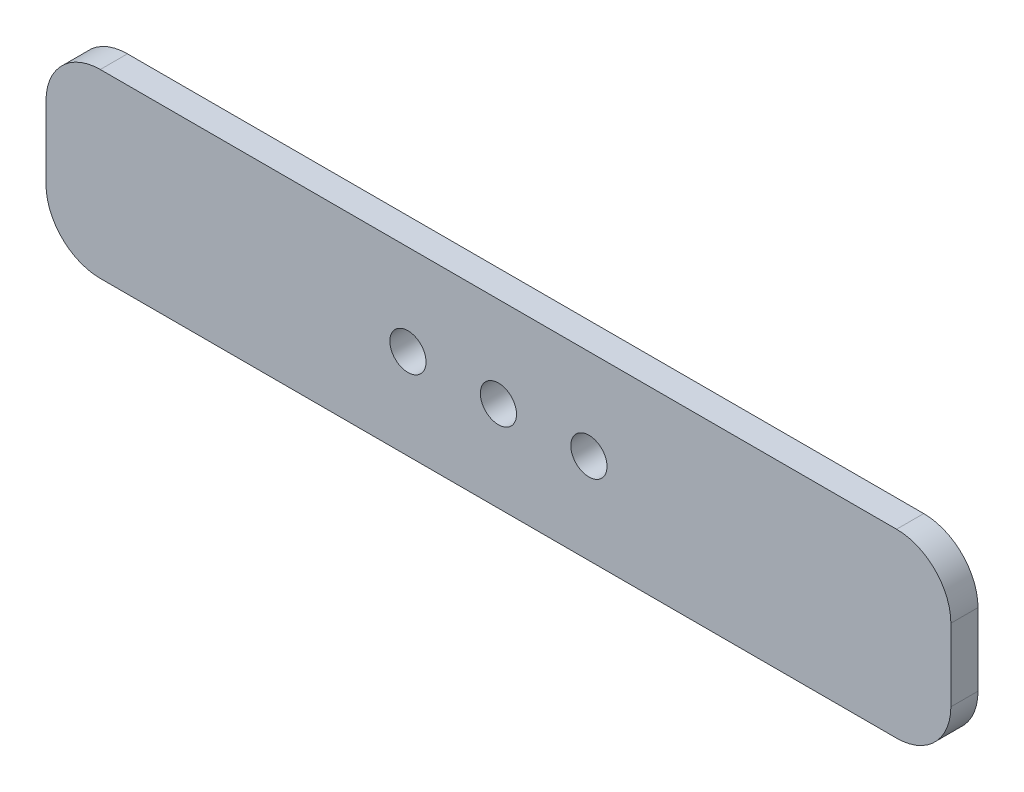
SolidWorks part; units mm, degrees
ref_plane "Plan de face" through (0, 0, 0) normal (0, 0, 1) x (1, 0, 0)
ref_plane "Plan de dessus" through (0, 0, 0) normal (0, 1, 0) x (1, 0, 0)
ref_plane "Plan de droite" through (0, 0, 0) normal (1, 0, 0) x (0, 0, -1)
sketch "Esquisse1" plane through (0, 0, 0) normal (0, 0, 1) x (1, 0, 0)
  line L1 (30, 0) -> (470, 0)
  line L2 (0, 30) -> (0, 70)
  line L3 (30, 100) -> (470, 100)
  line L4 (500, 30) -> (500, 70)
  arc A0 (470, 0) -> (500, 30) centre (470, 30) ccw
  arc A1 (30, 0) -> (0, 30) centre (30, 30) cw
  arc A2 (0, 70) -> (30, 100) centre (30, 70) cw
  arc A3 (500, 70) -> (470, 100) centre (470, 70) ccw
  point P9 (0, 0)
  point P12 (0, 100)
  point P15 (500, 100)
  dimension "D3" = 30
  dimension "D1" = 100
  dimension "D2" = 500
extrude "Boss.-Extru.1" add sketch "Esquisse1" along normal blind 15
sketch "Esquisse2" plane through (0, 0, 15) normal (0, 0, 1) x (1, 0, 0)
  line L0 (200, 50) -> (300, 50) construction
  line L5 (470, 100) -> (30, 100) construction
  line L7 (0, 70) -> (0, 30) construction
  circle A0 centre (200, 50) radius 10
  circle A3 centre (250, 50) radius 10
  circle A4 centre (300, 50) radius 10
  dimension "D1" = 50
  dimension "D3" = 20
  dimension "D2" = 200
  dimension "D4" = 50
  dimension "D5" = 50
extrude "Enlèv. mat.-Extru.2" cut sketch "Esquisse2" against normal through all
sketch "Esquisse3" plane through (0, 0, 0) normal (0, -1, 0) x (1, 0, 0)
  line L0 (30, 0) -> (470, 0) construction
  line L1 (30, 15) -> (30, 0) construction
  line L3 (470, 15) -> (470, 0) construction
  circle A0 centre (60, 7.5) radius 3
  circle A1 centre (440, 7.5) radius 3
  dimension "D1" = 6
  dimension "D3" = 30
  dimension "D4" = 30
  dimension "D5" = 7.5
  dimension "D2" = 7.5
extrude "Enlèv. mat.-Extru.3" cut sketch "Esquisse3" against normal blind 20
sketch "Esquisse4" plane through (0, 0, 15) normal (0, 0, 1) x (1, 0, 0)
  line L0 (470, 100) -> (30, 100) construction
  line L1 (0, 70) -> (0, 30) construction
  text T0 "                          MAQUETTE DE TEST \r\nSYSTEME DE CONTROLE DE TEMPERATURE DANS UN FOUR" font "Century Gothic" height 3.5
  point P1 (0, 0)
  dimension "D1" = 15
  dimension "D2" = 400
sketch "Esquisse5" plane through (0, 0, 15) normal (0, 0, 1) x (1, 0, 0)
  line L0 (30, 0) -> (470, 0) construction
  line L1 (0, 70) -> (0, 30) construction
  text T0 "<b>IMHAMED BOUJEMAA </b>" font "Century Gothic" height 3.5
  dimension "D1" = 5
  dimension "D2" = 140
sketch "Esquisse6" plane through (0, 0, 15) normal (0, 0, 1) x (1, 0, 0)
  line L0 (30, 0) -> (470, 0) construction
  line L1 (0, 70) -> (0, 30) construction
  text T0 "SYSTEME EN \r\n    ARRET"
  text T1 "SYSTEME EN \r\n    PLEINE \r\n  CHARGE"
  dimension "D1" = 32
  dimension "D2" = 213
  dimension "D3" = 32
  dimension "D4" = 263
sketch "Esquisse7" plane through (0, 0, 15) normal (0, 0, 1) x (1, 0, 0)
  line L1 (30, 0) -> (470, 0) construction
  line L2 (0, 70) -> (0, 30) construction
  text T0 "    SYSTEME \r\nEN MARCHE"
  point P1 (146.3237, 27.0749)
  point P2 (311.5111, 31.0423)
  dimension "D1" = 32
  dimension "D2" = 313
